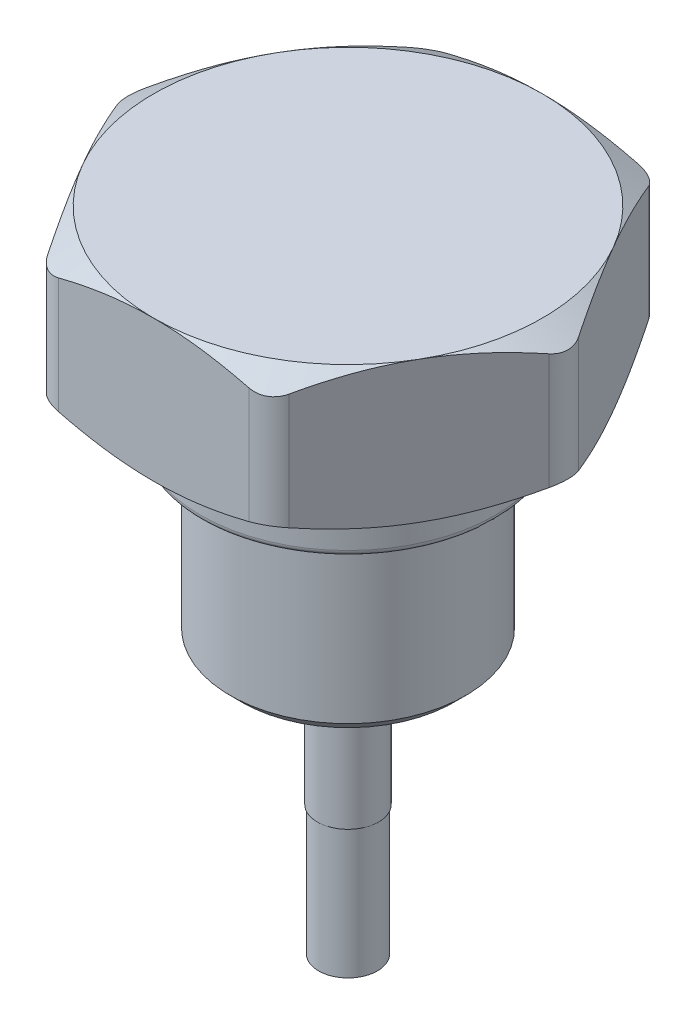
SolidWorks part; units mm, degrees
ref_plane "Ön Düzlem" through (0, 0, 0) normal (0, 0, 1) x (1, 0, 0)
ref_plane "Üst Düzlem" through (0, 0, 0) normal (0, 1, 0) x (1, 0, 0)
ref_plane "Sağ Düzlem" through (0, 0, 0) normal (1, 0, 0) x (0, 0, -1)
sketch "Sketch3" plane through (0, 0, 0) normal (0, 1, 0) x (1, 0, 0)
  line L1 (19.0526, 0) -> (9.5263, 16.5)
  line L2 (9.5263, 16.5) -> (-9.5263, 16.5)
  line L3 (-9.5263, 16.5) -> (-19.0526, 0)
  line L4 (-19.0526, 0) -> (-9.5263, -16.5)
  line L5 (-9.5263, -16.5) -> (9.5263, -16.5)
  line L6 (9.5263, -16.5) -> (19.0526, 0)
  circle A0 centre (0, 0) radius 16.5 construction
  dimension "D1" = 33
extrude "Boss-Extrude2" add sketch "Sketch3" along normal blind 12
sketch "Sketch4" plane through (0, 12, 0) normal (0, 1, 0) x (1, 0, 0)
  line L0 (19.0526, 0) -> (9.5263, 16.5) construction
  circle A0 centre (0, 0) radius 16.5
extrude "Cut-Extrude6" cut sketch "Sketch4" against normal blind 12 draft 60 flip side to cut
sketch "Sketch5" plane through (0, 0, 0) normal (0, -1, 0) x (1, 0, 0)
  line L0 (9.5263, 16.5) -> (19.0526, 0) construction
  circle A0 centre (0, 0) radius 16.5
extrude "Cut-Extrude7" cut sketch "Sketch5" against normal blind 12 draft 60 flip side to cut
fillet "Fillet1" radius 2.5 6 edges at (-19.0526, 6, 0) (-9.5263, 6, -16.5) (9.5263, 6, -16.5) (19.0526, 6, 0) (-9.5263, 6, 16.5) (9.5263, 6, 16.5)
sketch "Sketch9" plane through (0, 0, 0) normal (0, -1, 0) x (1, 0, 0)
  circle A0 centre (0, 0) radius 12.5
  dimension "D1" = 25
extrude "Boss-Extrude6" add sketch "Sketch9" along normal blind 5
sketch "Sketch11" plane through (0, -5, 0) normal (0, -1, 0) x (1, 0, 0)
  circle A0 centre (0, 0) radius 10
  dimension "D1" = 20
extrude "Boss-Extrude8" add sketch "Sketch11" along normal blind 15
chamfer "Chamfer1" distance 1 angle 45 1 edges at (0, -20, -10)
fillet "Fillet2" radius 0.5 2 edges at (0, -5, -12.5) (0, 0, 12.5)
sketch "Sketch12" plane through (0, -20, 0) normal (0, -1, 0) x (1, 0, 0)
  circle A0 centre (0, 0) radius 2.6
  dimension "D1" = 5.2
extrude "Boss-Extrude9" add sketch "Sketch12" along normal blind 12
sketch "Sketch13" plane through (0, -32, 0) normal (0, -1, 0) x (1, 0, 0)
  circle A0 centre (0, 0) radius 2.5
  dimension "D1" = 5
extrude "Boss-Extrude10" add sketch "Sketch13" along normal blind 11
